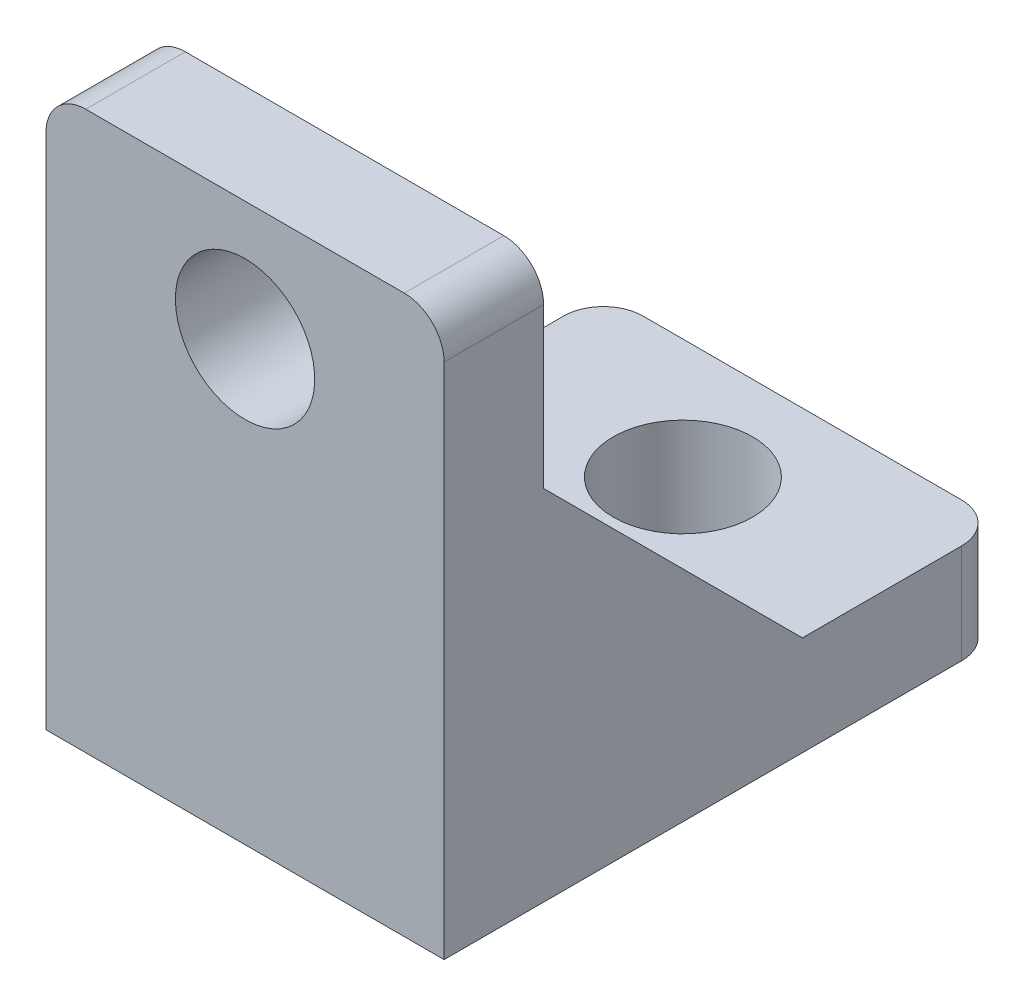
SolidWorks part; units mm, degrees
ref_plane "Front Plane" through (0, 0, 0) normal (0, 0, 1) x (1, 0, 0)
ref_plane "Top Plane" through (0, 0, 0) normal (0, 1, 0) x (1, 0, 0)
ref_plane "Right Plane" through (0, 0, 0) normal (1, 0, 0) x (0, 0, -1)
sketch "Sketch3" plane through (0, 0, 0) normal (1, 0, 0) x (0, 0, -1)
  line L0 (0, 0) -> (0, 28)
  line L1 (0, 28) -> (5, 28)
  line L2 (5, 28) -> (5, 5)
  line L3 (5, 5) -> (28, 5)
  line L4 (28, 5) -> (28, 0)
  line L5 (28, 0) -> (0, 0)
  dimension "D1" = 28
  dimension "D2" = 28
  dimension "D3" = 5
  dimension "D4" = 5
extrude "Boss-Extrude3" add sketch "Sketch3" along normal blind 20
sketch "Sketch4" plane through (20, 0, 0) normal (1, 0, 0) x (0, 0, -1)
  line L0 (5, 18) -> (5, 5)
  line L1 (5, 5) -> (5, 28) construction
  line L2 (5, 5) -> (18, 5)
  line L3 (28, 5) -> (5, 5) construction
  line L4 (18, 5) -> (5, 18)
  dimension "D1" = 13
  dimension "D2" = 13
extrude "Boss-Extrude4" add sketch "Sketch4" against normal blind 3
sketch "Sketch5" plane through (0, 0, 0) normal (-1, 0, 0) x (0, 0, 1)
  line L0 (-5, 18) -> (-5, 5)
  line L1 (-5, 18) -> (-5, 5) construction
  line L2 (-5, 5) -> (-18, 5)
  line L3 (-28, 5) -> (-5, 5) construction
  line L4 (-18, 5) -> (-5, 18)
  dimension "D1" = 13
  dimension "D2" = 13
extrude "Boss-Extrude5" add sketch "Sketch5" against normal blind 3
fillet "Fillet5" radius 2 5 edges at (0, 28, -2.5) (20, 28, -2.5) (10, 5, -5) (0, 2.5, -28) (20, 2.5, -28)
sketch "Sketch6" plane through (0, 0, -5) normal (0, 0, -1) x (-1, 0, 0)
  line L0 (-18, 28) -> (-2, 28) construction
  circle A0 centre (-10, 22) radius 3.5
  dimension "D1" = 7
  dimension "D2" = 6
extrude "Cut-Extrude1" cut sketch "Sketch6" against normal up to next
sketch "Sketch7" plane through (0, 5, 0) normal (0, 1, 0) x (1, 0, 0)
  line L0 (18, 28) -> (2, 28) construction
  circle A0 centre (10, 22) radius 3.5
  dimension "D1" = 7
  dimension "D2" = 6
extrude "Cut-Extrude2" cut sketch "Sketch7" against normal up to next
